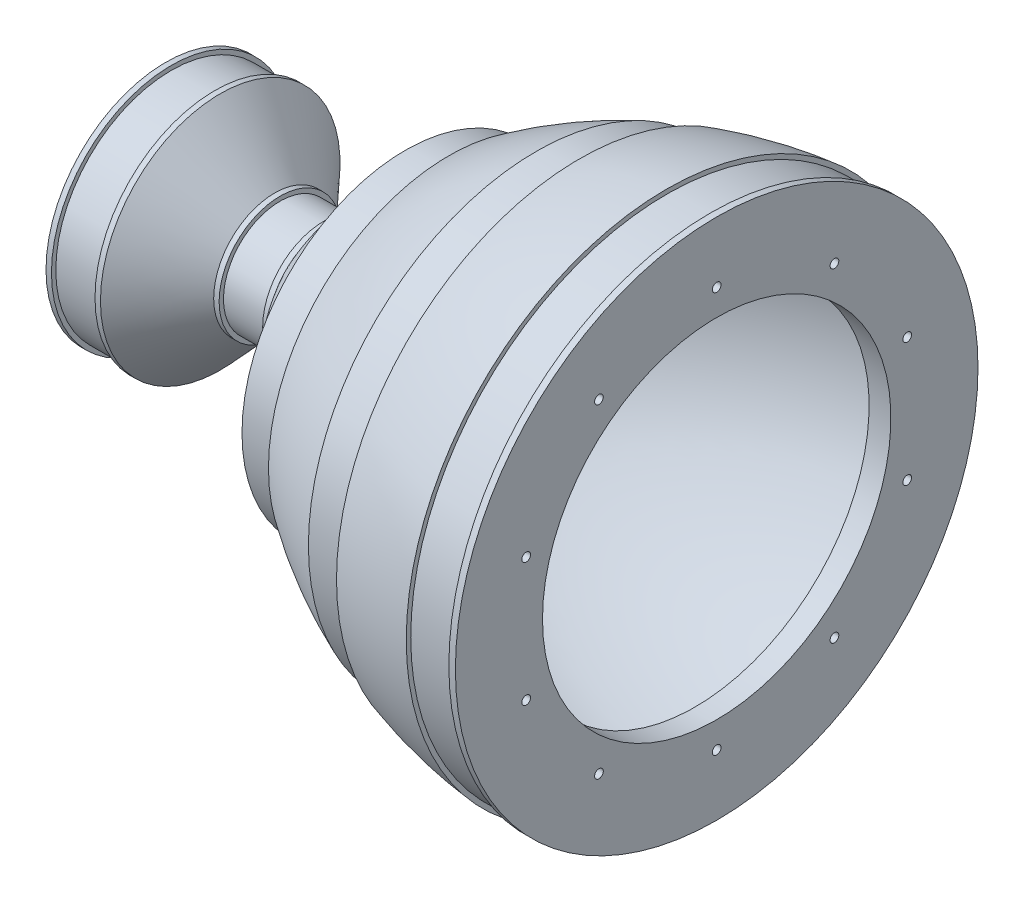
SolidWorks part; units mm, degrees
ref_plane "Front Plane" through (0, 0, 0) normal (0, 0, 1) x (1, 0, 0)
ref_plane "Top Plane" through (0, 0, 0) normal (0, 1, 0) x (1, 0, 0)
ref_plane "Right Plane" through (0, 0, 0) normal (1, 0, 0) x (0, 0, -1)
sketch "Sketch1" plane through (0, 0, 0) normal (0, 0, 1) x (1, 0, 0)
  line L0 (-129.7619, 0) -> (169.7619, 0) construction
  line L1 (-13.5477, 80) -> (-3.5477, 80)
  line L2 (-3.5477, 80) -> (-3.5477, 120)
  line L3 (-13.5477, 80) -> (-13.5477, 110)
  line L4 (-181.5477, 28) -> (-184.0477, 28)
  line L5 (-206.5477, 28) -> (-231.5477, 55)
  line L6 (-231.5477, 55) -> (-234.0477, 55)
  line L7 (-256.5477, 55) -> (-256.5477, 30)
  line L8 (-256.5477, 30) -> (-246.5477, 30)
  line L9 (-246.5477, 30) -> (-246.5477, 45.8203)
  line L10 (-246.5477, 45.8203) -> (-236.5477, 45.8203)
  line L12 (-212.64, 20) -> (-236.5477, 45.8203)
  line L14 (-6.5477, 120) -> (-6.5477, 117.5)
  line L15 (-6.5477, 117.5) -> (-26.5477, 117.5)
  line L16 (-26.5477, 117.5) -> (-26.5477, 119.5633)
  line L17 (-3.5477, 120) -> (-6.5477, 120)
  line L18 (-66.5477, 111.5964) -> (-66.5477, 104.5)
  line L19 (-66.5477, 104.5) -> (-86.5477, 104.5)
  line L20 (-126.5477, 82.8385) -> (-126.5477, 75)
  line L21 (-126.5477, 75) -> (-146.5477, 75)
  line L22 (-146.5477, 75) -> (-146.5477, 67.2754)
  line L23 (-204.0477, 28) -> (-204.0477, 26)
  line L24 (-204.0477, 26) -> (-184.0477, 26)
  line L25 (-184.0477, 26) -> (-184.0477, 28)
  line L26 (-254.0477, 55) -> (-254.0477, 53)
  line L27 (-254.0477, 53) -> (-234.0477, 53)
  line L28 (-234.0477, 53) -> (-234.0477, 55)
  line L29 (-175.5477, 20) -> (-212.64, 20)
  line L30 (-254.0477, 55) -> (-256.5477, 55)
  line L31 (-204.0477, 28) -> (-206.5477, 28)
  arc A1 (-13.5477, 110) -> (-175.5477, 20) centre (-5.7414, -94.8513) ccw
  arc A3 (-26.5477, 119.5633) -> (-66.5477, 111.5964) centre (-4.7402, -94.3279) ccw
  arc A4 (-146.5477, 67.2754) -> (-181.5477, 28) centre (-4.7402, -94.3279) ccw
  arc A5 (-86.5477, 104.5) -> (-126.5477, 82.8385) centre (-4.7402, -94.3279) ccw
  dimension "D3" = 215
  dimension "D4" = 205
  dimension "D15" = 2.5
  dimension "D18" = 10
  dimension "D21" = 10
  dimension "D1" = 10
  dimension "D2" = 120
  dimension "D5" = 25
  dimension "D6" = 10
  dimension "D7" = 10
  dimension "D8" = 8
  dimension "D9" = 25
  dimension "D10" = 25
  dimension "D11" = 20
  dimension "D12" = 253
  dimension "D13" = 80
  dimension "D14" = 55
  dimension "D16" = 20
  dimension "D17" = 3
  dimension "D19" = 63
  dimension "D20" = 20
  dimension "D22" = 104.5
  dimension "D23" = 40
  dimension "D24" = 75
  dimension "D25" = 20
  dimension "D26" = 20
  dimension "D27" = 2
  dimension "D28" = 20
  dimension "D29" = 2
  dimension "D30" = 25
revolve "Revolve1" add sketch "Sketch1" angle 360 about L0
sketch "Sketch2" plane through (-3.5477, 0, 0) normal (1, 0, 0) x (0, 0, -1)
  circle A0 centre (0, 92) radius 2
  circle A1 centre (54.0762, 74.4296) radius 2
  circle A2 centre (87.4972, 28.4296) radius 2
  circle A3 centre (87.4972, -28.4296) radius 2
  circle A4 centre (54.0762, -74.4296) radius 2
  circle A5 centre (0, -92) radius 2
  circle A6 centre (-54.0762, -74.4296) radius 2
  circle A7 centre (-87.4972, -28.4296) radius 2
  circle A8 centre (-87.4972, 28.4296) radius 2
  circle A9 centre (-54.0762, 74.4296) radius 2
  point P24 (0, 0)
  dimension "D1" = 4
  dimension "D2" = 92
  dimension "D3" = 10
extrude "Cut-Extrude1" cut sketch "Sketch2" against normal blind 10
sketch "Sketch3" plane through (-256.5477, 0, 0) normal (-1, 0, 0) x (0, 0, 1)
  circle A0 centre (0, 47.5) radius 2
  circle A1 centre (27.9198, 38.4283) radius 2
  circle A2 centre (45.1752, 14.6783) radius 2
  circle A3 centre (45.1752, -14.6783) radius 2
  circle A4 centre (27.9198, -38.4283) radius 2
  circle A5 centre (0, -47.5) radius 2
  circle A6 centre (-27.9198, -38.4283) radius 2
  circle A7 centre (-45.1752, -14.6783) radius 2
  circle A8 centre (-45.1752, 14.6783) radius 2
  circle A9 centre (-27.9198, 38.4283) radius 2
  point P24 (0, 0)
  dimension "D1" = 4
  dimension "D2" = 47.5
  dimension "D3" = 10
extrude "Cut-Extrude2" cut sketch "Sketch3" against normal blind 10
